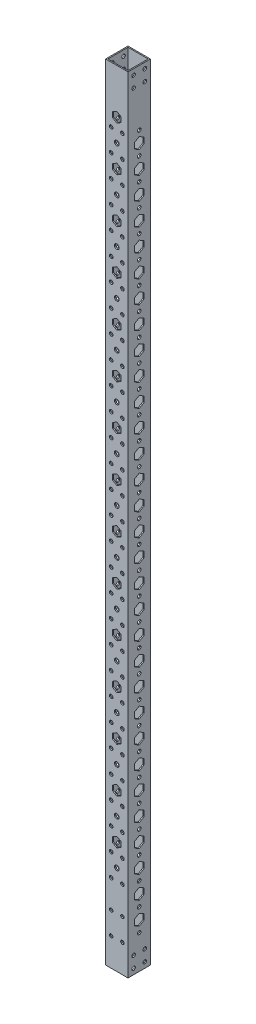
SolidWorks part; units mm, degrees
ref_plane "前视基准面" through (0, 0, 0) normal (0, 0, 1) x (1, 0, 0)
ref_plane "上视基准面" through (0, 0, 0) normal (0, 1, 0) x (1, 0, 0)
ref_plane "右视基准面" through (0, 0, 0) normal (1, 0, 0) x (0, 0, -1)
other "Configuration Table"
sketch "草图1" plane through (0, 0, 0) normal (0, 1, 0) x (1, 0, 0)
  line L1 (-10, -10) -> (10, -10)
  line L2 (-10, -10) -> (-10, 10)
  line L3 (-10, 10) -> (10, 10)
  line L4 (10, -10) -> (10, 10)
  line L5 (-10, -10) -> (10, 10) construction
  line L6 (-10, 10) -> (10, -10) construction
  point P0 (0, 0)
  dimension "D1" = 20
  dimension "D2" = 20
extrude "拉伸-薄壁1" add sketch "草图1" along normal blind 700 thin thin type one direction reverse wall 1
sketch "草图2" plane through (10, 0, 0) normal (1, 0, 0) x (0, 0, -1)
  line L0 (10, 700) -> (10, 0) construction
  line L1 (-10, 700) -> (10, 700)
  line L2 (-10, 700) -> (-10, 680)
  line L3 (-10, 680) -> (10, 680)
  line L4 (10, 700) -> (10, 680)
  line L6 (-10, 0) -> (10, 0)
  line L7 (-10, 0) -> (-10, 20)
  line L8 (-10, 20) -> (10, 20)
  line L9 (10, 0) -> (10, 20)
  dimension "D1" = 20
  dimension "D2" = 20
sketch "草图3" plane through (0, 0, 10) normal (0, 0, -1) x (-1, 0, 0)
  line L0 (0, 0) -> (0, 80) construction
  line L1 (-10, 35) -> (10, 35) construction
  line L2 (-10, 80) -> (10, 80) construction
  line L3 (0, 120) -> (0, 80) construction
  line L4 (0, 144.5) -> (-3.8971, 142.25)
  line L5 (0, 104.5) -> (-3.8971, 102.25)
  line L6 (-10, 700) -> (-10, 0) construction
  line L7 (10, 700) -> (10, 0) construction
  line L8 (-10, 0) -> (10, 0) construction
  line L9 (-3.8971, 102.25) -> (-3.8971, 97.75)
  line L10 (-3.8971, 97.75) -> (0, 95.5)
  line L11 (0, 95.5) -> (3.8971, 97.75)
  line L12 (3.8971, 97.75) -> (3.8971, 102.25)
  line L13 (3.8971, 102.25) -> (0, 104.5)
  line L14 (3.8971, 142.25) -> (0, 144.5)
  line L15 (3.8971, 137.75) -> (3.8971, 142.25)
  line L16 (0, 135.5) -> (3.8971, 137.75)
  line L17 (-3.8971, 137.75) -> (0, 135.5)
  line L18 (-3.8971, 142.25) -> (-3.8971, 137.75)
  line L19 (0, 184.5) -> (-3.8971, 182.25)
  line L20 (3.8971, 182.25) -> (0, 184.5)
  line L21 (3.8971, 177.75) -> (3.8971, 182.25)
  line L22 (0, 175.5) -> (3.8971, 177.75)
  line L23 (-3.8971, 177.75) -> (0, 175.5)
  line L24 (-3.8971, 182.25) -> (-3.8971, 177.75)
  line L25 (0, 224.5) -> (-3.8971, 222.25)
  line L26 (3.8971, 222.25) -> (0, 224.5)
  line L27 (3.8971, 217.75) -> (3.8971, 222.25)
  line L28 (0, 215.5) -> (3.8971, 217.75)
  line L29 (-3.8971, 217.75) -> (0, 215.5)
  line L30 (-3.8971, 222.25) -> (-3.8971, 217.75)
  line L31 (0, 264.5) -> (-3.8971, 262.25)
  line L32 (3.8971, 262.25) -> (0, 264.5)
  line L33 (3.8971, 257.75) -> (3.8971, 262.25)
  line L34 (0, 255.5) -> (3.8971, 257.75)
  line L35 (-3.8971, 257.75) -> (0, 255.5)
  line L36 (-3.8971, 262.25) -> (-3.8971, 257.75)
  line L37 (0, 304.5) -> (-3.8971, 302.25)
  line L38 (3.8971, 302.25) -> (0, 304.5)
  line L39 (3.8971, 297.75) -> (3.8971, 302.25)
  line L40 (0, 295.5) -> (3.8971, 297.75)
  line L41 (-3.8971, 297.75) -> (0, 295.5)
  line L42 (-3.8971, 302.25) -> (-3.8971, 297.75)
  line L43 (0, 344.5) -> (-3.8971, 342.25)
  line L44 (3.8971, 342.25) -> (0, 344.5)
  line L45 (3.8971, 337.75) -> (3.8971, 342.25)
  line L46 (0, 335.5) -> (3.8971, 337.75)
  line L47 (-3.8971, 337.75) -> (0, 335.5)
  line L48 (-3.8971, 342.25) -> (-3.8971, 337.75)
  line L49 (0, 384.5) -> (-3.8971, 382.25)
  line L50 (3.8971, 382.25) -> (0, 384.5)
  line L51 (3.8971, 377.75) -> (3.8971, 382.25)
  line L52 (0, 375.5) -> (3.8971, 377.75)
  line L53 (-3.8971, 377.75) -> (0, 375.5)
  line L54 (-3.8971, 382.25) -> (-3.8971, 377.75)
  line L55 (0, 424.5) -> (-3.8971, 422.25)
  line L56 (3.8971, 422.25) -> (0, 424.5)
  line L57 (3.8971, 417.75) -> (3.8971, 422.25)
  line L58 (0, 415.5) -> (3.8971, 417.75)
  line L59 (-3.8971, 417.75) -> (0, 415.5)
  line L60 (-3.8971, 422.25) -> (-3.8971, 417.75)
  line L61 (0, 464.5) -> (-3.8971, 462.25)
  line L62 (3.8971, 462.25) -> (0, 464.5)
  line L63 (3.8971, 457.75) -> (3.8971, 462.25)
  line L64 (0, 455.5) -> (3.8971, 457.75)
  line L65 (-3.8971, 457.75) -> (0, 455.5)
  line L66 (-3.8971, 462.25) -> (-3.8971, 457.75)
  line L67 (0, 504.5) -> (-3.8971, 502.25)
  line L68 (3.8971, 502.25) -> (0, 504.5)
  line L69 (3.8971, 497.75) -> (3.8971, 502.25)
  line L70 (0, 495.5) -> (3.8971, 497.75)
  line L71 (-3.8971, 497.75) -> (0, 495.5)
  line L72 (-3.8971, 502.25) -> (-3.8971, 497.75)
  line L73 (0, 544.5) -> (-3.8971, 542.25)
  line L74 (3.8971, 542.25) -> (0, 544.5)
  line L75 (3.8971, 537.75) -> (3.8971, 542.25)
  line L76 (0, 535.5) -> (3.8971, 537.75)
  line L77 (-3.8971, 537.75) -> (0, 535.5)
  line L78 (-3.8971, 542.25) -> (-3.8971, 537.75)
  line L79 (0, 584.5) -> (-3.8971, 582.25)
  line L80 (3.8971, 582.25) -> (0, 584.5)
  line L81 (3.8971, 577.75) -> (3.8971, 582.25)
  line L82 (0, 575.5) -> (3.8971, 577.75)
  line L83 (-3.8971, 577.75) -> (0, 575.5)
  line L84 (-3.8971, 582.25) -> (-3.8971, 577.75)
  line L85 (0, 624.5) -> (-3.8971, 622.25)
  line L86 (3.8971, 622.25) -> (0, 624.5)
  line L87 (3.8971, 617.75) -> (3.8971, 622.25)
  line L88 (0, 615.5) -> (3.8971, 617.75)
  line L89 (-3.8971, 617.75) -> (0, 615.5)
  line L90 (-3.8971, 622.25) -> (-3.8971, 617.75)
  line L91 (0, 664.5) -> (-3.8971, 662.25)
  line L92 (3.8971, 662.25) -> (0, 664.5)
  line L93 (3.8971, 657.75) -> (3.8971, 662.25)
  line L94 (0, 655.5) -> (3.8971, 657.75)
  line L95 (-3.8971, 657.75) -> (0, 655.5)
  line L96 (-3.8971, 662.25) -> (-3.8971, 657.75)
  circle A0 centre (-5, 25) radius 1.55
  circle A3 centre (-5, 45) radius 1.55
  circle A4 centre (5, 25) radius 1.55
  circle A5 centre (5, 45) radius 1.55
  circle A6 centre (0, 80) radius 2.1
  circle A7 centre (-5, 70) radius 1.6
  circle A8 centre (5, 70) radius 1.6
  circle A9 centre (5, 90) radius 1.6
  circle A10 centre (-5, 90) radius 1.6
  circle A11 centre (-5, 130) radius 1.6
  circle A12 centre (5, 130) radius 1.6
  circle A13 centre (0, 120) radius 2.1
  circle A14 centre (-5, 110) radius 1.6
  circle A15 centre (5, 110) radius 1.6
  circle A16 centre (-5, 170) radius 1.6
  circle A17 centre (5, 170) radius 1.6
  circle A18 centre (0, 160) radius 2.1
  circle A19 centre (-5, 150) radius 1.6
  circle A20 centre (5, 150) radius 1.6
  circle A21 centre (-5, 210) radius 1.6
  circle A22 centre (5, 210) radius 1.6
  circle A23 centre (0, 200) radius 2.1
  circle A24 centre (-5, 190) radius 1.6
  circle A25 centre (5, 190) radius 1.6
  circle A26 centre (-5, 250) radius 1.6
  circle A27 centre (5, 250) radius 1.6
  circle A28 centre (0, 240) radius 2.1
  circle A29 centre (-5, 230) radius 1.6
  circle A30 centre (5, 230) radius 1.6
  circle A31 centre (-5, 290) radius 1.6
  circle A32 centre (5, 290) radius 1.6
  circle A33 centre (0, 280) radius 2.1
  circle A34 centre (-5, 270) radius 1.6
  circle A35 centre (5, 270) radius 1.6
  circle A36 centre (-5, 330) radius 1.6
  circle A37 centre (5, 330) radius 1.6
  circle A38 centre (0, 320) radius 2.1
  circle A39 centre (-5, 310) radius 1.6
  circle A40 centre (5, 310) radius 1.6
  circle A41 centre (-5, 370) radius 1.6
  circle A42 centre (5, 370) radius 1.6
  circle A43 centre (0, 360) radius 2.1
  circle A44 centre (-5, 350) radius 1.6
  circle A45 centre (5, 350) radius 1.6
  circle A46 centre (-5, 410) radius 1.6
  circle A47 centre (5, 410) radius 1.6
  circle A48 centre (0, 400) radius 2.1
  circle A49 centre (-5, 390) radius 1.6
  circle A50 centre (5, 390) radius 1.6
  circle A51 centre (-5, 450) radius 1.6
  circle A52 centre (5, 450) radius 1.6
  circle A53 centre (0, 440) radius 2.1
  circle A54 centre (-5, 430) radius 1.6
  circle A55 centre (5, 430) radius 1.6
  circle A56 centre (-5, 490) radius 1.6
  circle A57 centre (5, 490) radius 1.6
  circle A58 centre (0, 480) radius 2.1
  circle A59 centre (-5, 470) radius 1.6
  circle A60 centre (5, 470) radius 1.6
  circle A61 centre (-5, 530) radius 1.6
  circle A62 centre (5, 530) radius 1.6
  circle A63 centre (0, 520) radius 2.1
  circle A64 centre (-5, 510) radius 1.6
  circle A65 centre (5, 510) radius 1.6
  circle A66 centre (-5, 570) radius 1.6
  circle A67 centre (5, 570) radius 1.6
  circle A68 centre (0, 560) radius 2.1
  circle A69 centre (-5, 550) radius 1.6
  circle A70 centre (5, 550) radius 1.6
  circle A71 centre (-5, 610) radius 1.6
  circle A72 centre (5, 610) radius 1.6
  circle A73 centre (0, 600) radius 2.1
  circle A74 centre (-5, 590) radius 1.6
  circle A75 centre (5, 590) radius 1.6
  circle A76 centre (-5, 650) radius 1.6
  circle A77 centre (5, 650) radius 1.6
  circle A78 centre (0, 640) radius 2.1
  circle A79 centre (-5, 630) radius 1.6
  circle A80 centre (5, 630) radius 1.6
  circle A81 centre (0, 100) radius 3.8971 construction
  circle A82 centre (0, 140) radius 3.8971 construction
  circle A83 centre (0, 180) radius 3.8971 construction
  circle A84 centre (0, 220) radius 3.8971 construction
  circle A85 centre (0, 260) radius 3.8971 construction
  circle A86 centre (0, 300) radius 3.8971 construction
  circle A87 centre (0, 340) radius 3.8971 construction
  circle A88 centre (0, 380) radius 3.8971 construction
  circle A89 centre (0, 420) radius 3.8971 construction
  circle A90 centre (0, 460) radius 3.8971 construction
  circle A91 centre (0, 500) radius 3.8971 construction
  circle A92 centre (0, 540) radius 3.8971 construction
  circle A93 centre (0, 580) radius 3.8971 construction
  circle A94 centre (0, 620) radius 3.8971 construction
  circle A95 centre (0, 660) radius 3.8971 construction
  dimension "D2" = 3.1
  dimension "D6" = 4.2
  dimension "D7" = 3.2
  dimension "D1" = 35
  dimension "D3" = 10
  dimension "D4" = 5
  dimension "D5" = 80
  dimension "D8" = 10
  dimension "D9" = 5
  dimension "D10" = 40
  dimension "D11" = 4.5
  dimension "D12" = 40
extrude "切除-拉伸2" cut sketch "草图3" along normal through all
sketch "草图4" plane through (10, 0, 0) normal (1, 0, 0) x (0, 0, -1)
  line L0 (-10, 10) -> (10, 10) construction
  line L1 (-10, 0) -> (-10, 20) construction
  line L2 (10, 0) -> (10, 20) construction
  line L3 (0, 0) -> (0, 20) construction
  line L4 (-10, 20) -> (10, 20) construction
  line L5 (10, 350) -> (-10, 350) construction
  line L6 (10, 700) -> (10, 0) construction
  line L7 (-10, 700) -> (-10, 0) construction
  line L8 (0, 700) -> (0, 680) construction
  line L9 (-10, 690) -> (10, 690) construction
  circle A0 centre (-5, 5) radius 1.6
  circle A1 centre (-5, 15) radius 1.6
  circle A2 centre (5, 5) radius 1.6
  circle A3 centre (5, 15) radius 1.6
  circle A4 centre (5, 685) radius 1.6
  circle A5 centre (5, 695) radius 1.6
  circle A6 centre (-5, 685) radius 1.6
  circle A7 centre (-5, 695) radius 1.6
  dimension "D1" = 3.2
  dimension "D2" = 5
  dimension "D3" = 5
extrude "切除-拉伸3" cut sketch "草图4" against normal through all
sketch "草图5" plane through (10, 0, 0) normal (1, 0, 0) x (0, 0, -1)
  line L0 (-10, 0) -> (10, 0) construction
  line L1 (0, 50) -> (0, 0) construction
  line L2 (0, 65) -> (-4.3301, 62.5)
  line L3 (0, 45) -> (-4.3301, 42.5)
  line L4 (-4.3301, 42.5) -> (-4.3301, 37.5)
  line L5 (-4.3301, 37.5) -> (0, 35)
  line L6 (0, 35) -> (4.3301, 37.5)
  line L7 (4.3301, 37.5) -> (4.3301, 42.5)
  line L8 (4.3301, 42.5) -> (0, 45)
  line L9 (4.3301, 57.5) -> (4.3301, 62.5)
  line L10 (4.3301, 62.5) -> (0, 65)
  line L11 (-4.3301, 57.5) -> (0, 55)
  line L12 (-4.3301, 62.5) -> (-4.3301, 57.5)
  line L13 (0, 55) -> (4.3301, 57.5)
  line L14 (0, 85) -> (-4.3301, 82.5)
  line L15 (4.3301, 77.5) -> (4.3301, 82.5)
  line L16 (4.3301, 82.5) -> (0, 85)
  line L17 (-4.3301, 77.5) -> (0, 75)
  line L18 (-4.3301, 82.5) -> (-4.3301, 77.5)
  line L19 (0, 75) -> (4.3301, 77.5)
  line L20 (0, 105) -> (-4.3301, 102.5)
  line L21 (4.3301, 97.5) -> (4.3301, 102.5)
  line L22 (4.3301, 102.5) -> (0, 105)
  line L23 (-4.3301, 97.5) -> (0, 95)
  line L24 (-4.3301, 102.5) -> (-4.3301, 97.5)
  line L25 (0, 95) -> (4.3301, 97.5)
  line L26 (0, 125) -> (-4.3301, 122.5)
  line L27 (4.3301, 117.5) -> (4.3301, 122.5)
  line L28 (4.3301, 122.5) -> (0, 125)
  line L29 (-4.3301, 117.5) -> (0, 115)
  line L30 (-4.3301, 122.5) -> (-4.3301, 117.5)
  line L31 (0, 115) -> (4.3301, 117.5)
  line L32 (0, 145) -> (-4.3301, 142.5)
  line L33 (4.3301, 137.5) -> (4.3301, 142.5)
  line L34 (4.3301, 142.5) -> (0, 145)
  line L35 (-4.3301, 137.5) -> (0, 135)
  line L36 (-4.3301, 142.5) -> (-4.3301, 137.5)
  line L37 (0, 135) -> (4.3301, 137.5)
  line L38 (0, 165) -> (-4.3301, 162.5)
  line L39 (4.3301, 157.5) -> (4.3301, 162.5)
  line L40 (4.3301, 162.5) -> (0, 165)
  line L41 (-4.3301, 157.5) -> (0, 155)
  line L42 (-4.3301, 162.5) -> (-4.3301, 157.5)
  line L43 (0, 155) -> (4.3301, 157.5)
  line L44 (0, 185) -> (-4.3301, 182.5)
  line L45 (4.3301, 177.5) -> (4.3301, 182.5)
  line L46 (4.3301, 182.5) -> (0, 185)
  line L47 (-4.3301, 177.5) -> (0, 175)
  line L48 (-4.3301, 182.5) -> (-4.3301, 177.5)
  line L49 (0, 175) -> (4.3301, 177.5)
  line L50 (0, 205) -> (-4.3301, 202.5)
  line L51 (4.3301, 197.5) -> (4.3301, 202.5)
  line L52 (4.3301, 202.5) -> (0, 205)
  line L53 (-4.3301, 197.5) -> (0, 195)
  line L54 (-4.3301, 202.5) -> (-4.3301, 197.5)
  line L55 (0, 195) -> (4.3301, 197.5)
  line L56 (0, 225) -> (-4.3301, 222.5)
  line L57 (4.3301, 217.5) -> (4.3301, 222.5)
  line L58 (4.3301, 222.5) -> (0, 225)
  line L59 (-4.3301, 217.5) -> (0, 215)
  line L60 (-4.3301, 222.5) -> (-4.3301, 217.5)
  line L61 (0, 215) -> (4.3301, 217.5)
  line L62 (0, 245) -> (-4.3301, 242.5)
  line L63 (4.3301, 237.5) -> (4.3301, 242.5)
  line L64 (4.3301, 242.5) -> (0, 245)
  line L65 (-4.3301, 237.5) -> (0, 235)
  line L66 (-4.3301, 242.5) -> (-4.3301, 237.5)
  line L67 (0, 235) -> (4.3301, 237.5)
  line L68 (0, 265) -> (-4.3301, 262.5)
  line L69 (4.3301, 257.5) -> (4.3301, 262.5)
  line L70 (4.3301, 262.5) -> (0, 265)
  line L71 (-4.3301, 257.5) -> (0, 255)
  line L72 (-4.3301, 262.5) -> (-4.3301, 257.5)
  line L73 (0, 255) -> (4.3301, 257.5)
  line L74 (0, 285) -> (-4.3301, 282.5)
  line L75 (4.3301, 277.5) -> (4.3301, 282.5)
  line L76 (4.3301, 282.5) -> (0, 285)
  line L77 (-4.3301, 277.5) -> (0, 275)
  line L78 (-4.3301, 282.5) -> (-4.3301, 277.5)
  line L79 (0, 275) -> (4.3301, 277.5)
  line L80 (0, 305) -> (-4.3301, 302.5)
  line L81 (4.3301, 297.5) -> (4.3301, 302.5)
  line L82 (4.3301, 302.5) -> (0, 305)
  line L83 (-4.3301, 297.5) -> (0, 295)
  line L84 (-4.3301, 302.5) -> (-4.3301, 297.5)
  line L85 (0, 295) -> (4.3301, 297.5)
  line L86 (0, 325) -> (-4.3301, 322.5)
  line L87 (4.3301, 317.5) -> (4.3301, 322.5)
  line L88 (4.3301, 322.5) -> (0, 325)
  line L89 (-4.3301, 317.5) -> (0, 315)
  line L90 (-4.3301, 322.5) -> (-4.3301, 317.5)
  line L91 (0, 315) -> (4.3301, 317.5)
  line L92 (0, 345) -> (-4.3301, 342.5)
  line L93 (4.3301, 337.5) -> (4.3301, 342.5)
  line L94 (4.3301, 342.5) -> (0, 345)
  line L95 (-4.3301, 337.5) -> (0, 335)
  line L96 (-4.3301, 342.5) -> (-4.3301, 337.5)
  line L97 (0, 335) -> (4.3301, 337.5)
  line L98 (0, 365) -> (-4.3301, 362.5)
  line L99 (4.3301, 357.5) -> (4.3301, 362.5)
  line L100 (4.3301, 362.5) -> (0, 365)
  line L101 (-4.3301, 357.5) -> (0, 355)
  line L102 (-4.3301, 362.5) -> (-4.3301, 357.5)
  line L103 (0, 355) -> (4.3301, 357.5)
  line L104 (0, 385) -> (-4.3301, 382.5)
  line L105 (4.3301, 377.5) -> (4.3301, 382.5)
  line L106 (4.3301, 382.5) -> (0, 385)
  line L107 (-4.3301, 377.5) -> (0, 375)
  line L108 (-4.3301, 382.5) -> (-4.3301, 377.5)
  line L109 (0, 375) -> (4.3301, 377.5)
  line L110 (0, 405) -> (-4.3301, 402.5)
  line L111 (4.3301, 397.5) -> (4.3301, 402.5)
  line L112 (4.3301, 402.5) -> (0, 405)
  line L113 (-4.3301, 397.5) -> (0, 395)
  line L114 (-4.3301, 402.5) -> (-4.3301, 397.5)
  line L115 (0, 395) -> (4.3301, 397.5)
  line L116 (0, 425) -> (-4.3301, 422.5)
  line L117 (4.3301, 417.5) -> (4.3301, 422.5)
  line L118 (4.3301, 422.5) -> (0, 425)
  line L119 (-4.3301, 417.5) -> (0, 415)
  line L120 (-4.3301, 422.5) -> (-4.3301, 417.5)
  line L121 (0, 415) -> (4.3301, 417.5)
  line L122 (0, 445) -> (-4.3301, 442.5)
  line L123 (4.3301, 437.5) -> (4.3301, 442.5)
  line L124 (4.3301, 442.5) -> (0, 445)
  line L125 (-4.3301, 437.5) -> (0, 435)
  line L126 (-4.3301, 442.5) -> (-4.3301, 437.5)
  line L127 (0, 435) -> (4.3301, 437.5)
  line L128 (0, 465) -> (-4.3301, 462.5)
  line L129 (4.3301, 457.5) -> (4.3301, 462.5)
  line L130 (4.3301, 462.5) -> (0, 465)
  line L131 (-4.3301, 457.5) -> (0, 455)
  line L132 (-4.3301, 462.5) -> (-4.3301, 457.5)
  line L133 (0, 455) -> (4.3301, 457.5)
  line L134 (0, 485) -> (-4.3301, 482.5)
  line L135 (4.3301, 477.5) -> (4.3301, 482.5)
  line L136 (4.3301, 482.5) -> (0, 485)
  line L137 (-4.3301, 477.5) -> (0, 475)
  line L138 (-4.3301, 482.5) -> (-4.3301, 477.5)
  line L139 (0, 475) -> (4.3301, 477.5)
  line L140 (0, 505) -> (-4.3301, 502.5)
  line L141 (4.3301, 497.5) -> (4.3301, 502.5)
  line L142 (4.3301, 502.5) -> (0, 505)
  line L143 (-4.3301, 497.5) -> (0, 495)
  line L144 (-4.3301, 502.5) -> (-4.3301, 497.5)
  line L145 (0, 495) -> (4.3301, 497.5)
  line L146 (0, 525) -> (-4.3301, 522.5)
  line L147 (4.3301, 517.5) -> (4.3301, 522.5)
  line L148 (4.3301, 522.5) -> (0, 525)
  line L149 (-4.3301, 517.5) -> (0, 515)
  line L150 (-4.3301, 522.5) -> (-4.3301, 517.5)
  line L151 (0, 515) -> (4.3301, 517.5)
  line L152 (0, 545) -> (-4.3301, 542.5)
  line L153 (4.3301, 537.5) -> (4.3301, 542.5)
  line L154 (4.3301, 542.5) -> (0, 545)
  line L155 (-4.3301, 537.5) -> (0, 535)
  line L156 (-4.3301, 542.5) -> (-4.3301, 537.5)
  line L157 (0, 535) -> (4.3301, 537.5)
  line L158 (0, 565) -> (-4.3301, 562.5)
  line L159 (4.3301, 557.5) -> (4.3301, 562.5)
  line L160 (4.3301, 562.5) -> (0, 565)
  line L161 (-4.3301, 557.5) -> (0, 555)
  line L162 (-4.3301, 562.5) -> (-4.3301, 557.5)
  line L163 (0, 555) -> (4.3301, 557.5)
  line L164 (0, 585) -> (-4.3301, 582.5)
  line L165 (4.3301, 577.5) -> (4.3301, 582.5)
  line L166 (4.3301, 582.5) -> (0, 585)
  line L167 (-4.3301, 577.5) -> (0, 575)
  line L168 (-4.3301, 582.5) -> (-4.3301, 577.5)
  line L169 (0, 575) -> (4.3301, 577.5)
  line L170 (0, 605) -> (-4.3301, 602.5)
  line L171 (4.3301, 597.5) -> (4.3301, 602.5)
  line L172 (4.3301, 602.5) -> (0, 605)
  line L173 (-4.3301, 597.5) -> (0, 595)
  line L174 (-4.3301, 602.5) -> (-4.3301, 597.5)
  line L175 (0, 595) -> (4.3301, 597.5)
  line L176 (0, 625) -> (-4.3301, 622.5)
  line L177 (4.3301, 617.5) -> (4.3301, 622.5)
  line L178 (4.3301, 622.5) -> (0, 625)
  line L179 (-4.3301, 617.5) -> (0, 615)
  line L180 (-4.3301, 622.5) -> (-4.3301, 617.5)
  line L181 (0, 615) -> (4.3301, 617.5)
  line L182 (0, 645) -> (-4.3301, 642.5)
  line L183 (4.3301, 637.5) -> (4.3301, 642.5)
  line L184 (4.3301, 642.5) -> (0, 645)
  line L185 (-4.3301, 637.5) -> (0, 635)
  line L186 (-4.3301, 642.5) -> (-4.3301, 637.5)
  line L187 (0, 635) -> (4.3301, 637.5)
  circle A0 centre (0, 50) radius 1.6
  circle A1 centre (0, 70) radius 1.6
  circle A2 centre (0, 90) radius 1.6
  circle A3 centre (0, 110) radius 1.6
  circle A4 centre (0, 130) radius 1.6
  circle A5 centre (0, 150) radius 1.6
  circle A6 centre (0, 170) radius 1.6
  circle A7 centre (0, 190) radius 1.6
  circle A8 centre (0, 210) radius 1.6
  circle A9 centre (0, 230) radius 1.6
  circle A10 centre (0, 250) radius 1.6
  circle A11 centre (0, 270) radius 1.6
  circle A12 centre (0, 290) radius 1.6
  circle A13 centre (0, 310) radius 1.6
  circle A14 centre (0, 330) radius 1.6
  circle A15 centre (0, 350) radius 1.6
  circle A16 centre (0, 370) radius 1.6
  circle A17 centre (0, 390) radius 1.6
  circle A18 centre (0, 410) radius 1.6
  circle A19 centre (0, 430) radius 1.6
  circle A20 centre (0, 450) radius 1.6
  circle A21 centre (0, 470) radius 1.6
  circle A22 centre (0, 490) radius 1.6
  circle A23 centre (0, 510) radius 1.6
  circle A24 centre (0, 530) radius 1.6
  circle A25 centre (0, 550) radius 1.6
  circle A26 centre (0, 570) radius 1.6
  circle A27 centre (0, 590) radius 1.6
  circle A28 centre (0, 610) radius 1.6
  circle A29 centre (0, 630) radius 1.6
  circle A30 centre (0, 650) radius 1.6
  circle A31 centre (0, 30) radius 1.6
  circle A32 centre (0, 40) radius 4.3301 construction
  circle A33 centre (0, 60) radius 4.3301 construction
  circle A34 centre (0, 80) radius 4.3301 construction
  circle A35 centre (0, 100) radius 4.3301 construction
  circle A36 centre (0, 120) radius 4.3301 construction
  circle A37 centre (0, 140) radius 4.3301 construction
  circle A38 centre (0, 160) radius 4.3301 construction
  circle A39 centre (0, 180) radius 4.3301 construction
  circle A40 centre (0, 200) radius 4.3301 construction
  circle A41 centre (0, 220) radius 4.3301 construction
  circle A42 centre (0, 240) radius 4.3301 construction
  circle A43 centre (0, 260) radius 4.3301 construction
  circle A44 centre (0, 280) radius 4.3301 construction
  circle A45 centre (0, 300) radius 4.3301 construction
  circle A46 centre (0, 320) radius 4.3301 construction
  circle A47 centre (0, 340) radius 4.3301 construction
  circle A48 centre (0, 360) radius 4.3301 construction
  circle A49 centre (0, 380) radius 4.3301 construction
  circle A50 centre (0, 400) radius 4.3301 construction
  circle A51 centre (0, 420) radius 4.3301 construction
  circle A52 centre (0, 440) radius 4.3301 construction
  circle A53 centre (0, 460) radius 4.3301 construction
  circle A54 centre (0, 480) radius 4.3301 construction
  circle A55 centre (0, 500) radius 4.3301 construction
  circle A56 centre (0, 520) radius 4.3301 construction
  circle A57 centre (0, 540) radius 4.3301 construction
  circle A58 centre (0, 560) radius 4.3301 construction
  circle A59 centre (0, 580) radius 4.3301 construction
  circle A60 centre (0, 600) radius 4.3301 construction
  circle A61 centre (0, 620) radius 4.3301 construction
  circle A62 centre (0, 640) radius 4.3301 construction
  dimension "D1" = 3.2
  dimension "D2" = 50
  dimension "D6" = 20
  dimension "D7" = 20
  dimension "D8" = 20
  dimension "D9" = 5
  dimension "D10" = 10
  dimension "D11" = 20
  dimension "D3" = 30
  dimension "D4" = 2
  dimension "D5" = 2
extrude "切除-拉伸4" cut sketch "草图5" against normal through all
